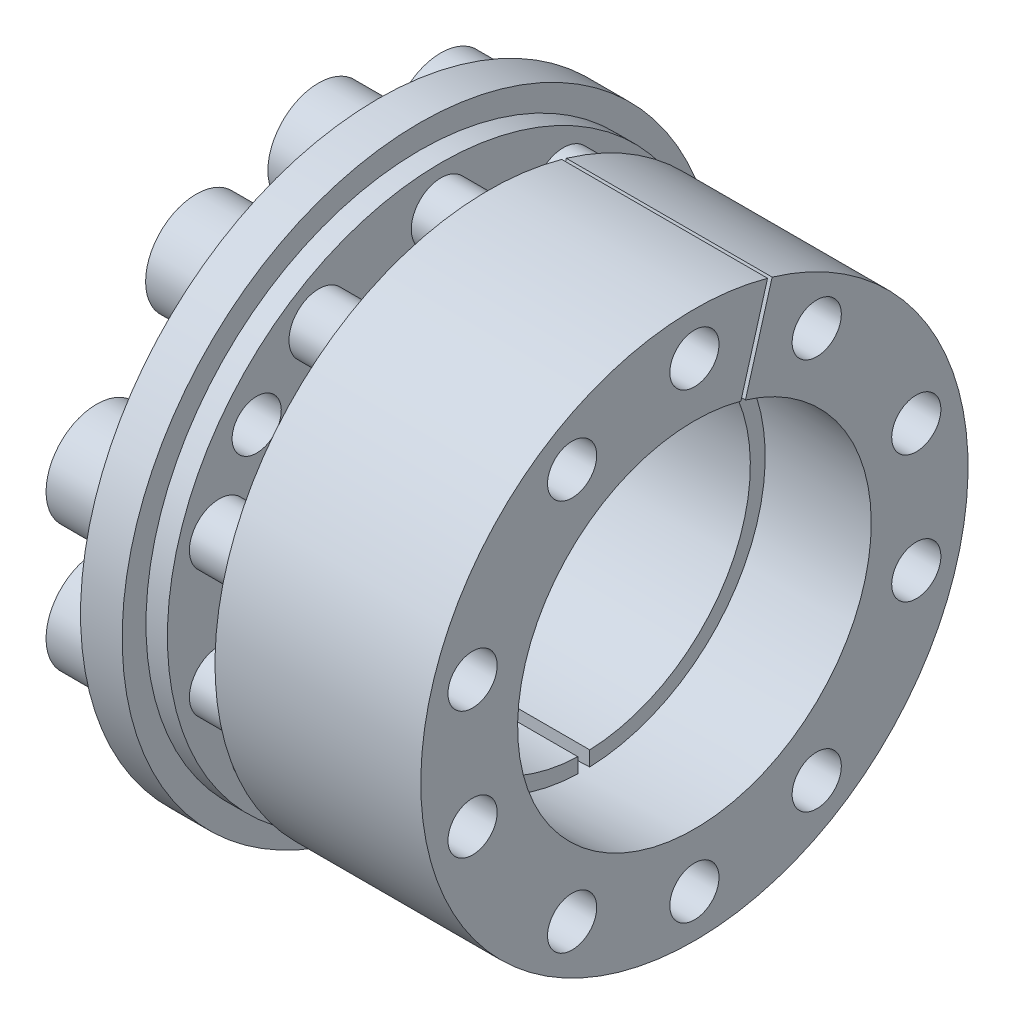
SolidWorks part; units mm, degrees
ref_plane "Front Plane" through (0, 0, 0) normal (0, 0, 1) x (1, 0, 0)
ref_plane "Top Plane" through (0, 0, 0) normal (0, 1, 0) x (1, 0, 0)
ref_plane "Right Plane" through (0, 0, 0) normal (1, 0, 0) x (0, 0, -1)
sketch "Sketch1" plane through (0, 0, 0) normal (0, 0, 1) x (1, 0, 0)
  line L0 (0, 0) -> (-26.6, 0) construction
  line L1 (-26.6, -14) -> (-9.3, -14)
  line L5 (-9.3, -15.25) -> (-21.3, -15.75)
  line L6 (-21.3, -15.75) -> (-21.3, -23)
  line L7 (-21.3, -23) -> (-23.1, -23)
  line L8 (-23.1, -23) -> (-23.1, -25)
  line L9 (-23.1, -25) -> (-26.6, -25)
  line L10 (-26.6, -25) -> (-26.6, -14)
  line L12 (-9.3, -15.25) -> (-9.3, -14)
  dimension "D_s" = 28
  dimension "D" = 46
  dimension "D1." = 50
  dimension "L2" = 26.6
  dimension "T" = 3.5
  dimension "T2" = 1.8
  dimension "MSM_1" = 31.5
  dimension "MSM_3" = 12
  dimension "MSM_2" = 30.5
revolve "Revolve1" add sketch "Sketch1" angle 360 about L0
sketch "Sketch2" plane through (-9.3, 0, 0) normal (1, 0, 0) x (0, 0, -1)
  line L0 (0, 0) -> (0, -15.75) construction
  line L1 (0.5, -13.9911) -> (0.5, -15.7421)
  line L2 (-0.5, -13.9911) -> (-0.5, -15.7421)
  circle A0 centre (0, 0) radius 15.75 construction
  circle A1 centre (0, 0) radius 14 construction
  arc A2 (-0.5, -13.9911) -> (0.5, -13.9911) centre (0, 0) ccw
  arc A3 (-0.5, -15.7421) -> (0.5, -15.7421) centre (0, 0) ccw
  dimension "FIX_2" = 1
extrude "Cut-Extrude1" cut sketch "Sketch2" against normal up to surface (12 mm away) up to face at (-21.3, 15.75, 0)
sketch "Sketch3" plane through (0, 0, 0) normal (0, 0, 1) x (1, 0, 0)
  line L0 (0, 0) -> (-26.6, 0) construction
  line L1 (-17.3, -15.5833) -> (0, -14.8625)
  line L2 (-9.3, -15.25) -> (-21.3, -15.75) construction
  line L3 (-17.3, -15.5833) -> (-17.3, -23)
  line L4 (-17.3, -23) -> (0, -23)
  line L5 (0, -14.8625) -> (0, -23)
  line L6 (-21.3, -23) -> (-23.1, -23) construction
  dimension "L3" = 17.3
revolve "Revolve2" add sketch "Sketch3" angle 360 about L0
sketch "Sketch4" plane through (0, 0, 0) normal (1, 0, 0) x (0, 0, -1)
  line L0 (0, 23) -> (0, -23) construction
  line L1 (0, 0) -> (6.3397, 22.109) construction
  line L2 (6.5317, 22.0531) -> (4.2885, 14.2303)
  line L3 (6.1472, 22.1633) -> (3.904, 14.3406)
  circle A0 centre (0, 0) radius 23 construction
  circle A1 centre (0, 0) radius 23 construction
  arc A2 (6.5317, 22.0531) -> (6.1472, 22.1633) centre (0, 0) ccw
  circle A3 centre (0, 0) radius 14.8625 construction
  arc A4 (4.2885, 14.2303) -> (3.904, 14.3406) centre (0, 0) ccw
  dimension "FIX_5" = 16
  dimension "FIX_4" = 0.4
sketch "Sketch5" plane through (-17.3, 0, 0) normal (-1, 0, 0) x (0, 0, 1)
  line L0 (-6.5317, 22.0531) -> (-4.4872, 14.9233)
  line L1 (-6.1472, 22.1633) -> (-4.1027, 15.0336)
  line L2 (-6.5317, 22.0531) -> (-4.2885, 14.2303) construction
  arc A0 (0.5, -15.5753) -> (-0.5, -15.5753) centre (0, 0) ccw construction
  circle A1 centre (0, 0) radius 23 construction
  arc A2 (-4.1027, 15.0336) -> (-4.4872, 14.9233) centre (0, 0) ccw
  arc A3 (-6.1472, 22.1633) -> (-6.5317, 22.0531) centre (0, 0) ccw
loft "Cut-Loft1" cut profiles "Sketch4", "Sketch5"
sketch "Sketch6" plane through (-26.6, 0, 0) normal (-1, 0, 0) x (0, 0, 1)
  line L0 (0, 19.4) -> (0, -19.4) construction
  line L1 (-10.2804, 16.4521) -> (10.2804, -16.4521) construction
  line L2 (10.2804, 16.4521) -> (-10.2804, -16.4521) construction
  line L3 (18.6485, -5.3474) -> (-18.6485, 5.3474) construction
  line L4 (18.6485, 5.3474) -> (-18.6485, -5.3474) construction
  circle A0 centre (0, 0) radius 19.4 construction
  circle A1 centre (0, 19.4) radius 4.25
  circle A2 centre (10.2804, -16.4521) radius 4.25
  circle A3 centre (0, -19.4) radius 4.25
  circle A4 centre (-10.2804, 16.4521) radius 4.25
  circle A5 centre (10.2804, 16.4521) radius 4.25
  circle A6 centre (-10.2804, -16.4521) radius 4.25
  circle A7 centre (-18.6485, 5.3474) radius 4.25
  circle A8 centre (18.6485, -5.3474) radius 4.25
  circle A9 centre (18.6485, 5.3474) radius 4.25
  circle A10 centre (-18.6485, -5.3474) radius 4.25
  dimension "P.C.D." = 38.8
  dimension "MSM_4" = 8.5
extrude "Boss-Extrude1" add sketch "Sketch6" along normal blind 5
sketch "Sketch7" plane through (-17.3, 0, 0) normal (-1, 0, 0) x (0, 0, 1)
  circle A0 centre (0, 19.4) radius 2.067
  circle A1 centre (10.2804, -16.4521) radius 2.067
  circle A2 centre (0, -19.4) radius 2.067
  circle A3 centre (-10.2804, 16.4521) radius 2.067
  circle A4 centre (10.2804, 16.4521) radius 2.067
  circle A5 centre (-10.2804, -16.4521) radius 2.067
  circle A6 centre (-18.6485, 5.3474) radius 2.067
  circle A7 centre (18.6485, -5.3474) radius 2.067
  circle A8 centre (18.6485, 5.3474) radius 2.067
  circle A9 centre (-18.6485, -5.3474) radius 2.067
  dimension "MSM_6" = 4.134
extrude "Cut-Extrude2" cut sketch "Sketch7" against normal through all
sketch "Sketch8" plane through (-26.6, 0, 0) normal (-1, 0, 0) x (0, 0, 1)
  circle A0 centre (0, 19.4) radius 2.5
  circle A1 centre (10.2804, -16.4521) radius 2.5
  circle A2 centre (0, -19.4) radius 2.5
  circle A3 centre (-10.2804, 16.4521) radius 2.5
  circle A4 centre (10.2804, 16.4521) radius 2.5
  circle A5 centre (-10.2804, -16.4521) radius 2.5
  circle A6 centre (-18.6485, 5.3474) radius 2.5
  circle A7 centre (18.6485, -5.3474) radius 2.5
  circle A8 centre (18.6485, 5.3474) radius 2.5
  circle A9 centre (-18.6485, -5.3474) radius 2.5
  dimension "MSM_7" = 5
extrude "Boss-Extrude2" add sketch "Sketch8" against normal blind 18
sketch "Sketch9" plane through (-31.6, 0, 0) normal (-1, 0, 0) x (0, 0, 1)
  line L0 (0, 21.4) -> (0, 17.4) construction
  line L1 (0, 21.7094) -> (-2, 20.5547)
  line L2 (-2, 20.5547) -> (-2, 18.2453)
  line L3 (-2, 18.2453) -> (0, 17.0906)
  line L4 (0, 17.0906) -> (2, 18.2453)
  line L5 (2, 18.2453) -> (2, 20.5547)
  line L6 (2, 20.5547) -> (0, 21.7094)
  line L7 (10.2804, -14.1427) -> (8.2804, -15.2974)
  line L8 (8.2804, -15.2974) -> (8.2804, -17.6068)
  line L9 (8.2804, -17.6068) -> (10.2804, -18.7615)
  line L10 (10.2804, -18.7615) -> (12.2804, -17.6068)
  line L11 (12.2804, -17.6068) -> (12.2804, -15.2974)
  line L12 (12.2804, -15.2974) -> (10.2804, -14.1427)
  line L13 (0, -17.0906) -> (-2, -18.2453)
  line L14 (-2, -18.2453) -> (-2, -20.5547)
  line L15 (-2, -20.5547) -> (0, -21.7094)
  line L16 (0, -21.7094) -> (2, -20.5547)
  line L17 (2, -20.5547) -> (2, -18.2453)
  line L18 (2, -18.2453) -> (0, -17.0906)
  line L19 (-10.2804, 18.7615) -> (-12.2804, 17.6068)
  line L20 (-12.2804, 17.6068) -> (-12.2804, 15.2974)
  line L21 (-12.2804, 15.2974) -> (-10.2804, 14.1427)
  line L22 (-10.2804, 14.1427) -> (-8.2804, 15.2974)
  line L23 (-8.2804, 15.2974) -> (-8.2804, 17.6068)
  line L24 (-8.2804, 17.6068) -> (-10.2804, 18.7615)
  line L25 (-2, 19.4) -> (2, 19.4) construction
  line L26 (10.2804, -14.4521) -> (10.2804, -18.4521) construction
  line L27 (8.2804, -16.4521) -> (12.2804, -16.4521) construction
  line L28 (0, -21.4) -> (0, -17.4) construction
  line L29 (-2, -19.4) -> (2, -19.4) construction
  line L30 (-12.2804, 16.4521) -> (-8.2804, 16.4521) construction
  line L31 (-10.2804, 18.4521) -> (-10.2804, 14.4521) construction
  line L32 (10.2804, 18.4521) -> (10.2804, 14.4521) construction
  line L33 (10.2804, 18.7615) -> (8.2804, 17.6068)
  line L34 (8.2804, 17.6068) -> (8.2804, 15.2974)
  line L35 (8.2804, 15.2974) -> (10.2804, 14.1427)
  line L36 (10.2804, 14.1427) -> (12.2804, 15.2974)
  line L37 (12.2804, 15.2974) -> (12.2804, 17.6068)
  line L38 (12.2804, 17.6068) -> (10.2804, 18.7615)
  line L39 (-10.2804, -14.1427) -> (-12.2804, -15.2974)
  line L40 (-12.2804, -15.2974) -> (-12.2804, -17.6068)
  line L41 (-12.2804, -17.6068) -> (-10.2804, -18.7615)
  line L42 (-10.2804, -18.7615) -> (-8.2804, -17.6068)
  line L43 (-8.2804, -17.6068) -> (-8.2804, -15.2974)
  line L44 (-8.2804, -15.2974) -> (-10.2804, -14.1427)
  line L45 (8.2804, 16.4521) -> (12.2804, 16.4521) construction
  line L46 (-10.2804, -14.4521) -> (-10.2804, -18.4521) construction
  line L47 (-12.2804, -16.4521) -> (-8.2804, -16.4521) construction
  line L48 (-18.6485, 7.3474) -> (-18.6485, 3.3474) construction
  line L49 (-18.6485, 7.6568) -> (-20.6485, 6.5021)
  line L50 (-20.6485, 6.5021) -> (-20.6485, 4.1927)
  line L51 (-20.6485, 4.1927) -> (-18.6485, 3.038)
  line L52 (-18.6485, 3.038) -> (-16.6485, 4.1927)
  line L53 (-16.6485, 4.1927) -> (-16.6485, 6.5021)
  line L54 (-16.6485, 6.5021) -> (-18.6485, 7.6568)
  line L55 (18.6485, -3.038) -> (16.6485, -4.1927)
  line L56 (16.6485, -4.1927) -> (16.6485, -6.5021)
  line L57 (16.6485, -6.5021) -> (18.6485, -7.6568)
  line L58 (18.6485, -7.6568) -> (20.6485, -6.5021)
  line L59 (20.6485, -6.5021) -> (20.6485, -4.1927)
  line L60 (20.6485, -4.1927) -> (18.6485, -3.038)
  line L61 (-20.6485, 5.3474) -> (-16.6485, 5.3474) construction
  line L62 (16.6485, -5.3474) -> (20.6485, -5.3474) construction
  line L63 (18.6485, -3.3474) -> (18.6485, -7.3474) construction
  line L64 (18.6485, 7.3474) -> (18.6485, 3.3474) construction
  line L65 (18.6485, 7.6568) -> (16.6485, 6.5021)
  line L66 (16.6485, 6.5021) -> (16.6485, 4.1927)
  line L67 (16.6485, 4.1927) -> (18.6485, 3.038)
  line L68 (18.6485, 3.038) -> (20.6485, 4.1927)
  line L69 (20.6485, 4.1927) -> (20.6485, 6.5021)
  line L70 (20.6485, 6.5021) -> (18.6485, 7.6568)
  line L71 (-18.6485, -3.038) -> (-20.6485, -4.1927)
  line L72 (-20.6485, -4.1927) -> (-20.6485, -6.5021)
  line L73 (-20.6485, -6.5021) -> (-18.6485, -7.6568)
  line L74 (-18.6485, -7.6568) -> (-16.6485, -6.5021)
  line L75 (-16.6485, -6.5021) -> (-16.6485, -4.1927)
  line L76 (-16.6485, -4.1927) -> (-18.6485, -3.038)
  line L77 (16.6485, 5.3474) -> (20.6485, 5.3474) construction
  line L78 (-18.6485, -3.3474) -> (-18.6485, -7.3474) construction
  line L79 (-20.6485, -5.3474) -> (-16.6485, -5.3474) construction
  circle A0 centre (0, 19.4) radius 2 construction
  circle A1 centre (10.2804, -16.4521) radius 2 construction
  circle A2 centre (0, -19.4) radius 2 construction
  circle A3 centre (-10.2804, 16.4521) radius 2 construction
  circle A4 centre (10.2804, 16.4521) radius 2 construction
  circle A5 centre (-10.2804, -16.4521) radius 2 construction
  circle A6 centre (-18.6485, 5.3474) radius 2 construction
  circle A7 centre (18.6485, -5.3474) radius 2 construction
  circle A8 centre (18.6485, 5.3474) radius 2 construction
  circle A9 centre (-18.6485, -5.3474) radius 2 construction
  dimension "MSM_9" = 4
extrude "Cut-Extrude3" cut sketch "Sketch9" against normal blind 2
hole_wizard "Tap1" positions "Sketch11" profile "Sketch10" hole size "M5x0.8" standard "JIS"
sketch "Sketch11" plane through (-26.6, 0, 0) normal (-1, 0, 0) x (0, 0, 1)
  line L0 (15.4935, 11.6752) -> (-15.4935, -11.6752) construction
  line L2 (0, 19.4) -> (0, -19.4) construction
  line L3 (-15.4935, 11.6752) -> (15.4935, -11.6752) construction
  line L4 (0, 19.4) -> (0, -19.4) construction
  circle A0 centre (0, 0) radius 19.4 construction
  point P0 (15.4935, 11.6752)
  point P2 (-15.4935, -11.6752)
  point P20 (-15.4935, 11.6752)
  point P21 (15.4935, -11.6752)
  dimension "FIX_8" = 53
sketch "Sketch10" plane through (-26.6, 11.6752, 15.4935) normal (0, 1, 0) x (0, 0, 1)
  line L0 (0, 0) -> (0, 5.3)
  line L1 (0, 5.3) -> (2.067, 5.3)
  line L2 (2.067, 5.3) -> (2.067, 0)
  line L5 (2.067, 0) -> (0, 0)
  line L11 (0, 0) -> (0, 5.3) construction
  dimension "STD_1" = 4.134
  dimension "Thru Hole Depth" = 5.3
cosmetic thread "Thread1" parameters "HTD_1"=5
cosmetic thread "Thread2" parameters "HTD_1"=5
cosmetic thread "Thread3" parameters "HTD_1"=5
cosmetic thread "Thread4" parameters "HTD_1"=5
